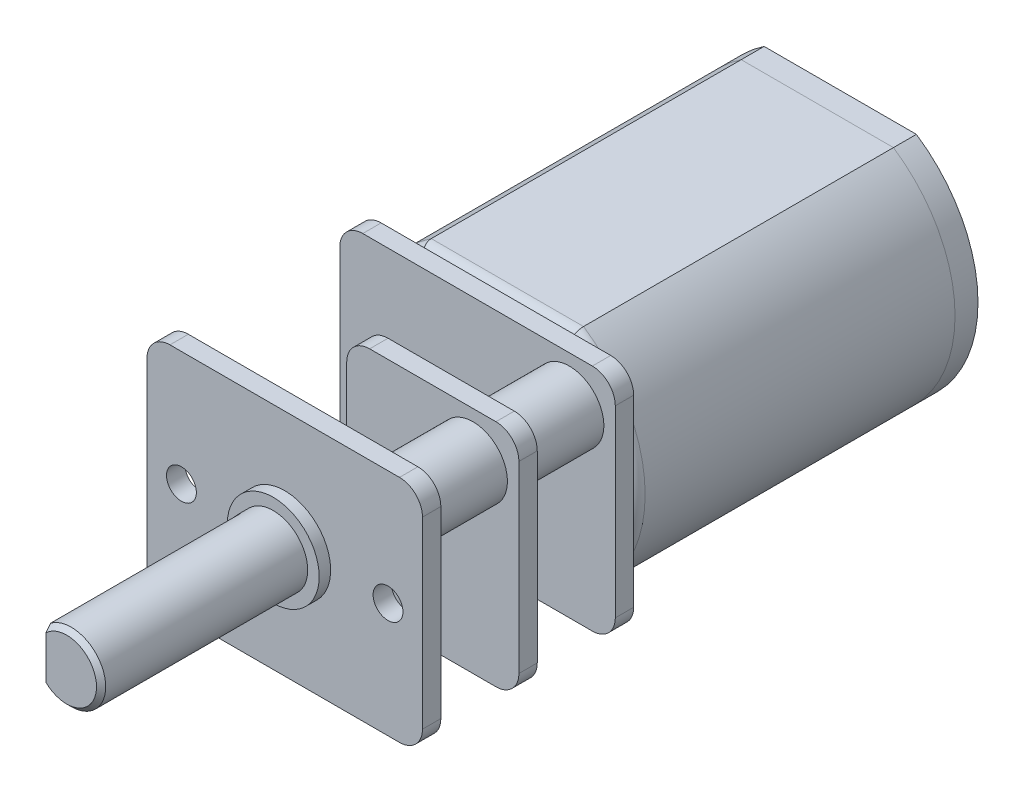
SolidWorks part; units mm, degrees
ref_plane "Front Plane" through (0, 0, 0) normal (0, 0, 1) x (1, 0, 0)
ref_plane "Top Plane" through (0, 0, 0) normal (0, 1, 0) x (1, 0, 0)
ref_plane "Right Plane" through (0, 0, 0) normal (1, 0, 0) x (0, 0, -1)
sketch "Sketch1" plane through (0, 0, 0) normal (0, 0, 1) x (1, 0, 0)
  line L0 (-3.3166, 5) -> (3.3166, 5)
  line L1 (3.3166, -5) -> (-3.3166, -5)
  arc A0 (3.3166, -5) -> (3.3166, 5) centre (0, 0) ccw
  arc A1 (-3.3166, 5) -> (-3.3166, -5) centre (0, 0) ccw
  dimension "D1" = 6
  dimension "D2" = 10
extrude "Boss-Extrude1" add sketch "Sketch1" against normal blind 14
sketch "Sketch2" plane through (0, 0, -14) normal (0, 0, -1) x (-1, 0, 0)
  line L4 (3.3166, 5) -> (-3.3166, 5)
  line L5 (-3.3166, -5) -> (3.3166, -5)
  line L6 (3.3166, 5) -> (-3.3166, 5)
  line L7 (-3.3166, -5) -> (3.3166, -5)
  arc A4 (3.3166, -5) -> (3.3166, 5) centre (0, 0) ccw
  arc A5 (-3.3166, 5) -> (-3.3166, -5) centre (0, 0) ccw
  arc A6 (3.3166, -5) -> (3.3166, 5) centre (0, 0) ccw
  arc A7 (-3.3166, 5) -> (-3.3166, -5) centre (0, 0) ccw
  dimension "D1" = 0
extrude "Boss-Extrude2" add sketch "Sketch2" along normal blind 1 separate body
sketch "Sketch3" plane through (0, 0, -15) normal (0, 0, -1) x (-1, 0, 0)
  circle A0 centre (0, 0) radius 2.5
  dimension "D1" = 5
extrude "Boss-Extrude3" add sketch "Sketch3" along normal blind 1
fillet "Fillet1" radius 0.5 4 edges at (0, 5, 0) (6, 0, 0) (0, -5, 0) (-6, 0, 0)
sketch "Sketch4" plane through (0, 0, -15) normal (0, 0, -1) x (-1, 0, 0)
  line L0 (3.5, 0) -> (0, 0) construction
  line L1 (-3.8, 0.75) -> (-3.5, 0.75)
  line L2 (-3.8, 0.75) -> (-3.8, -0.75)
  line L3 (-3.8, -0.75) -> (-3.5, -0.75)
  line L4 (-3.5, 0.75) -> (-3.5, -0.75)
  line L5 (3.5, 0.75) -> (3.8, 0.75)
  line L6 (3.5, 0.75) -> (3.5, -0.75)
  line L7 (3.5, -0.75) -> (3.8, -0.75)
  line L8 (3.8, 0.75) -> (3.8, -0.75)
  line L9 (0, 0) -> (-3.5, 0) construction
  dimension "D1" = 0.3
  dimension "D2" = 1.5
  dimension "D3" = 7
extrude "Boss-Extrude4" add sketch "Sketch4" along normal blind 1.5 separate body
sketch "Sketch5" plane through (0, 0, -16) normal (0, 0, -1) x (-1, 0, 0)
  circle A0 centre (0, 0) radius 1
  dimension "D1" = 2
extrude "Cut-Extrude1" cut sketch "Sketch5" against normal blind 1
sketch "Sketch6" plane through (0, 0, 0) normal (0, 0, 1) x (1, 0, 0)
  line L0 (-5, 4) -> (5, -4) construction
  line L1 (-5, 5) -> (5, 5)
  line L2 (-6, 4) -> (-6, -4)
  line L3 (-5, -5) -> (5, -5)
  line L4 (6, 4) -> (6, -4)
  arc A0 (5, 5) -> (6, 4) centre (5, 4) cw
  arc A1 (-6, -4) -> (-5, -5) centre (-5, -4) ccw
  arc A2 (5, -5) -> (6, -4) centre (5, -4) ccw
  arc A3 (-5, 5) -> (-6, 4) centre (-5, 4) ccw
  dimension "D1" = 1
  dimension "D2" = 10
  dimension "D3" = 12
extrude "Boss-Extrude5" add sketch "Sketch6" along normal blind 0.8 separate body
pattern_linear "LPattern1" count 2 spacing 4.2 along (0, 0, 1) of "Boss-Extrude5"
pattern_linear "LPattern2" count 2 spacing 8.4 along (0, 0, 1) of "Boss-Extrude5"
sketch "Sketch7" plane through (0, 0, 0.8) normal (0, 0, 1) x (1, 0, 0)
  line L0 (-4, -3) -> (4, 3) construction
  circle A0 centre (4, 3) radius 1.5
  circle A1 centre (-4, -3) radius 1.5
  dimension "D1" = 3
  dimension "D3" = 3
  dimension "D2" = 4
extrude "Boss-Extrude6" add sketch "Sketch7" along normal up to surface (8.4 mm away) up to face at (0, 0, 9.2)
sketch "Sketch8" plane through (0, 0, 9.2) normal (0, 0, 1) x (1, 0, 0)
  circle A0 centre (0, 0) radius 2
  dimension "D1" = 4
extrude "Boss-Extrude7" add sketch "Sketch8" along normal blind 0.5
sketch "Sketch9" plane through (0, 0, 9.7) normal (0, 0, 1) x (1, 0, 0)
  circle A0 centre (0, 0) radius 1.5
  dimension "D1" = 3
extrude "Boss-Extrude8" add sketch "Sketch9" along normal blind 9 separate body
sketch "Sketch10" plane through (0, 0, 18.7) normal (0, 0, 1) x (1, 0, 0)
  line L1 (-0.9, 1.2) -> (-1.5, 1.2)
  line L2 (-0.9, 1.2) -> (-0.9, -1.2)
  line L3 (-0.9, -1.2) -> (-1.5, -1.2)
  line L4 (-1.5, 1.2) -> (-1.5, -1.2)
  circle A0 centre (0, 0) radius 1.5 construction
  dimension "D1" = 2.4
extrude "Cut-Extrude2" cut sketch "Sketch10" against normal blind 8.5
chamfer "Chamfer1" distance 0.2 angle 45 1 edges at (1.5, 0, 18.7)
sketch "Sketch11" plane through (0, 0, 9.2) normal (0, 0, 1) x (1, 0, 0)
  line L0 (4.5, 0) -> (-4.5, 0) construction
  circle A0 centre (-4.5, 0) radius 0.65
  circle A1 centre (4.5, 0) radius 0.65
  dimension "D1" = 1.3
  dimension "D2" = 9
extrude "Cut-Extrude3" cut sketch "Sketch11" against normal up to next (0.8 mm away)
sketch "Sketch12" plane through (0, 0, 5) normal (0, 0, 1) x (1, 0, 0)
  line L0 (5, 5) -> (-5, 5) construction
  line L1 (-6, 5) -> (-1.5, 5)
  line L2 (-6, 5) -> (-6, 0)
  line L3 (-6, 0) -> (-1.5, 0)
  line L4 (-1.5, 5) -> (-1.5, 0)
  line L5 (-6, 4) -> (-6, -4) construction
  line L6 (6, -4) -> (6, 4) construction
  line L7 (-5, -5) -> (5, -5) construction
  dimension "D1" = 5
  dimension "D2" = 7.5
extrude "Cut-Extrude4" cut sketch "Sketch12" against normal up to next (0.8 mm away)
fillet "Fillet2" radius 1 3 edges at (-1.5, 0, 4.6) (-1.5, 5, 4.6) (-6, 0, 4.6)
